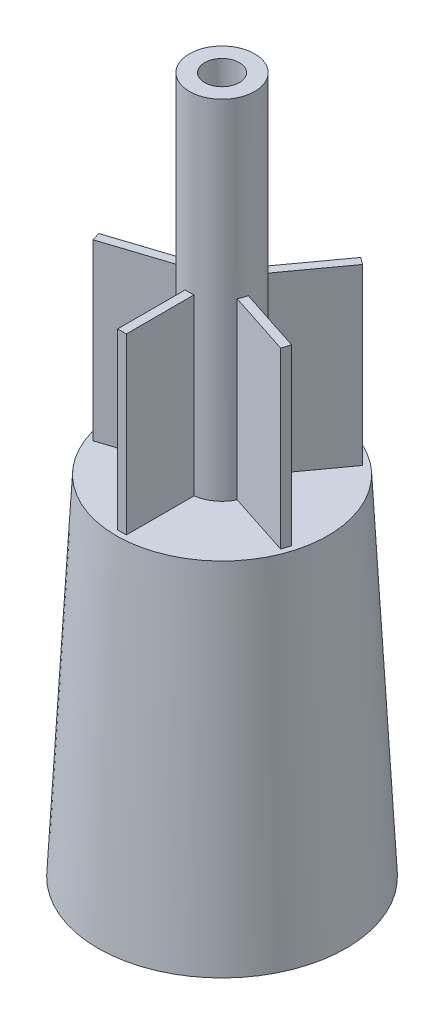
SolidWorks part; units mm, degrees
ref_plane "Front Plane" through (0, 0, 0) normal (0, 0, 1) x (1, 0, 0)
ref_plane "Top Plane" through (0, 0, 0) normal (0, 1, 0) x (1, 0, 0)
ref_plane "Right Plane" through (0, 0, 0) normal (1, 0, 0) x (0, 0, -1)
sketch "Sketch1" plane through (0, 0, 0) normal (0, 1, 0) x (1, 0, 0)
  circle A0 centre (0, 0) radius 2.85
  dimension "D1" = 5.7
extrude "Extrude1" add sketch "Sketch1" along normal blind 8 draft 3
shell "Shell1" thickness 0.5
sketch "Sketch3" plane through (0, 8, 0) normal (0, 1, 0) x (-1, 0, 0)
  circle A0 centre (0, 0) radius 0.75
  dimension "D1" = 1.5
extrude "Extrude2" add sketch "Sketch3" along normal blind 8
sketch "Sketch4" plane through (0, 8, 0) normal (0, 1, 0) x (-1, 0, 0)
  line L0 (0, 0) -> (0, 3.7994) construction
  line L1 (0, 0) -> (-3.3141, 0) construction
  line L2 (0.6645, 0.3235) -> (2.1542, 0.8075)
  line L3 (0.727, 0.1335) -> (2.216, 0.6173)
  line L4 (-0.1, 0.7323) -> (-0.1, 2.3)
  line L5 (-0.1, 2.3) -> (0.1, 2.3)
  line L6 (0.1, 0.7323) -> (0.1, 2.3)
  line L7 (2.1542, 0.8075) -> (2.216, 0.6173)
  line L8 (0.5124, -0.5327) -> (1.4314, -1.7975)
  line L9 (0.3508, -0.6505) -> (1.2696, -1.9151)
  line L10 (1.4314, -1.7975) -> (1.2696, -1.9151)
  line L11 (-0.3508, -0.6505) -> (-1.2696, -1.9151)
  line L12 (-0.5124, -0.5327) -> (-1.4314, -1.7975)
  line L13 (-1.2696, -1.9151) -> (-1.4314, -1.7975)
  line L14 (-0.727, 0.1335) -> (-2.216, 0.6173)
  line L15 (-0.6645, 0.3235) -> (-2.1542, 0.8075)
  line L16 (-2.216, 0.6173) -> (-2.1542, 0.8075)
  arc A0 (-0.6645, 0.3235) -> (-0.727, 0.1335) centre (0, 0) ccw
  arc A1 (-0.5124, -0.5327) -> (-0.3508, -0.6505) centre (0, 0) ccw
  arc A2 (0.1, 0.7323) -> (-0.1, 0.7323) centre (0, 0) ccw
  arc A3 (0.727, 0.1335) -> (0.6645, 0.3235) centre (0, 0) ccw
  arc A4 (0.3508, -0.6505) -> (0.5124, -0.5327) centre (0, 0) ccw
  dimension "D1" = 0.1
  dimension "D2" = 0.1
  dimension "D3" = 2.3
extrude "Extrude3" add sketch "Sketch4" along normal blind 4
sketch "Sketch5" plane through (0, 7.5, 0) normal (0, -1, 0) x (1, 0, 0)
  circle A0 centre (0, 0) radius 0.3985
extrude "Cut-Extrude1" cut sketch "Sketch5" against normal through all
